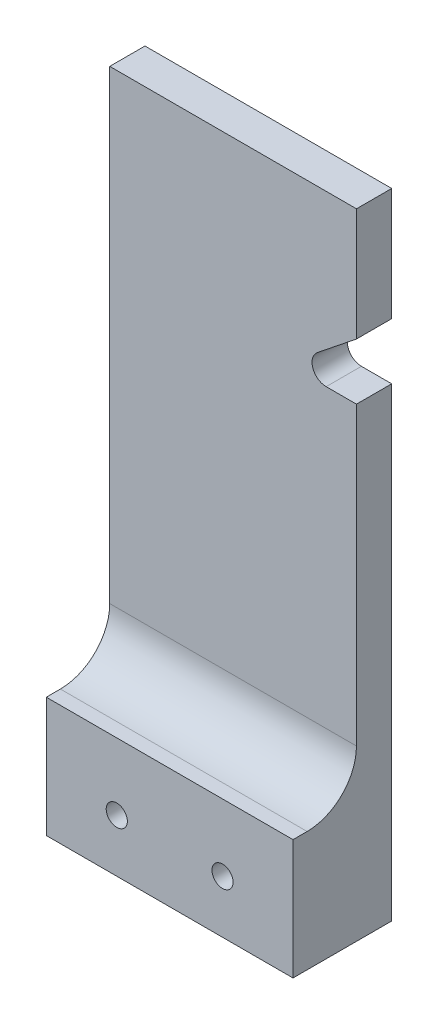
SolidWorks part; units mm, degrees
ref_plane "前视基准面" through (0, 0, 0) normal (0, 0, 1) x (1, 0, 0)
ref_plane "上视基准面" through (0, 0, 0) normal (0, 1, 0) x (1, 0, 0)
ref_plane "右视基准面" through (0, 0, 0) normal (1, 0, 0) x (0, 0, -1)
other "Configuration Table"
sketch "草图1" plane through (0, 0, 0) normal (0, 0, 1) x (1, 0, 0)
  line L1 (-17.5, -45) -> (17.5, -45)
  line L2 (-17.5, -45) -> (-17.5, 45)
  line L3 (-17.5, 45) -> (17.5, 45)
  line L4 (17.5, -45) -> (17.5, 45)
  line L5 (-17.5, -45) -> (17.5, 45) construction
  line L6 (-17.5, 45) -> (17.5, -45) construction
  point P0 (0, 0)
  dimension "D1" = 90
  dimension "D2" = 35
extrude "凸台-拉伸1" add sketch "草图1" along normal blind 5
sketch "草图2" plane through (0, 0, 5) normal (0, 0, 1) x (1, 0, 0)
  line L0 (17.5, -45) -> (17.5, 45) construction
  line L1 (-17.5, -45) -> (17.5, -45)
  line L2 (-17.5, -45) -> (-17.5, -28)
  line L3 (-17.5, -28) -> (17.5, -28)
  line L4 (17.5, -45) -> (17.5, -28)
  dimension "D1" = 17
extrude "凸台-拉伸2" add sketch "草图2" along normal blind 9
fillet "圆角1" radius 7 1 edges at (0, -28, 5)
sketch "草图3" plane through (0, 0, 14) normal (0, 0, 1) x (1, 0, 0)
  line L0 (-17.5, -28) -> (-17.5, -45) construction
  line L1 (17.5, -45) -> (17.5, -28) construction
  line L2 (-17.5, -45) -> (17.5, -45) construction
  circle A0 centre (-7.5, -37.5) radius 1.5
  circle A1 centre (7.5, -37.5) radius 1.5
  dimension "D1" = 3
  dimension "D2" = 3
  dimension "D3" = 10
  dimension "D4" = 10
  dimension "D5" = 7.5
  dimension "D6" = 7.5
extrude "切除-拉伸3" cut sketch "草图3" against normal through all
sketch "草图4" plane through (0, 0, 0) normal (0, 0, -1) x (-1, 0, 0)
  line L0 (-17.5, 29) -> (-17.5, 21)
  line L1 (-17.5, -45) -> (-17.5, 45) construction
  line L2 (-17.5, 21) -> (-7.5, 21)
  line L3 (-7.5, 21) -> (-17.5, 29)
  line L4 (-17.5, 45) -> (17.5, 45) construction
  dimension "D1" = 8
  dimension "D2" = 8
  dimension "D3" = 10
  dimension "D4" = 16
extrude "切除-拉伸4" cut sketch "草图4" against normal through all
fillet "圆角2" radius 2 1 edges at (7.5, 21, 2.5)
